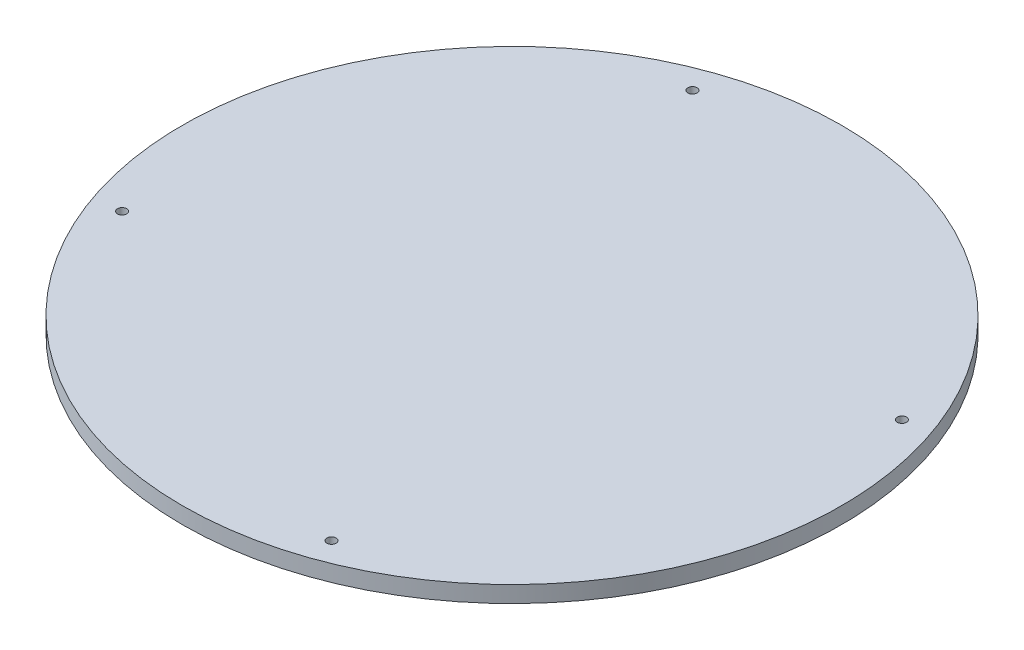
SolidWorks part; units mm, degrees
material "Pine"
ref_plane "Front Plane" through (0, 0, 0) normal (0, 0, 1) x (1, 0, 0)
ref_plane "Top Plane" through (0, 0, 0) normal (0, 1, 0) x (1, 0, 0)
ref_plane "Right Plane" through (0, 0, 0) normal (1, 0, 0) x (0, 0, -1)
sketch "Sketch1" plane through (0, 0, 0) normal (0, 1, 0) x (1, 0, 0)
  circle A0 centre (0, 0) radius 50
  dimension "D1" = 100
extrude "Boss-Extrude1" add sketch "Sketch1" along normal blind 2.5
sketch "Sketch2" plane through (0, 0, 0) normal (0, -1, 0) x (1, 0, 0)
  point P0 (-15.891, -43.2705)
  point P4 (-43.2705, 15.891)
  point P5 (15.891, 43.2705)
  point P6 (43.2705, -15.891)
  point P7 (0, 0)
  dimension "D1" = 4
hole_wizard "CBORE for #00 Binding Head Machine Screw1" positions "3DSketch1" profile "Sketch3" counterbore size "#00" standard "ANSI Inch"
sketch3d "3DSketch1"
  point P0 (-15.891, 0, -43.2705)
  point P3 (-43.2705, 0, 15.891)
  point P6 (15.891, 0, 43.2705)
  point P9 (43.2705, 0, -15.891)
sketch "Sketch3" plane through (-15.891, 0, -43.2705) normal (1, 0, 0) x (0, 0, -1)
  line L0 (0, 0) -> (0, 7.9197)
  line L1 (0, 7.9197) -> (0.6985, 7.5)
  line L2 (0.6985, 7.5) -> (0.6985, 0.7112)
  line L3 (0.6985, 0.7112) -> (1.5875, 0.7112)
  line L4 (1.5875, 0.7112) -> (1.5875, 0)
  line L5 (1.5875, 0) -> (0, 0)
  line L10 (0, 7.9197) -> (-0.6985, 7.5) construction
  line L11 (0, -6.35) -> (0, 107.95) construction
  dimension "Hole Dia." = 1.397
  dimension "Hole Depth" = 7.5
  dimension "C'Bore Dia." = 3.175
  dimension "C'Bore Depth" = 0.7112
  dimension "Drill Angle" = 118
